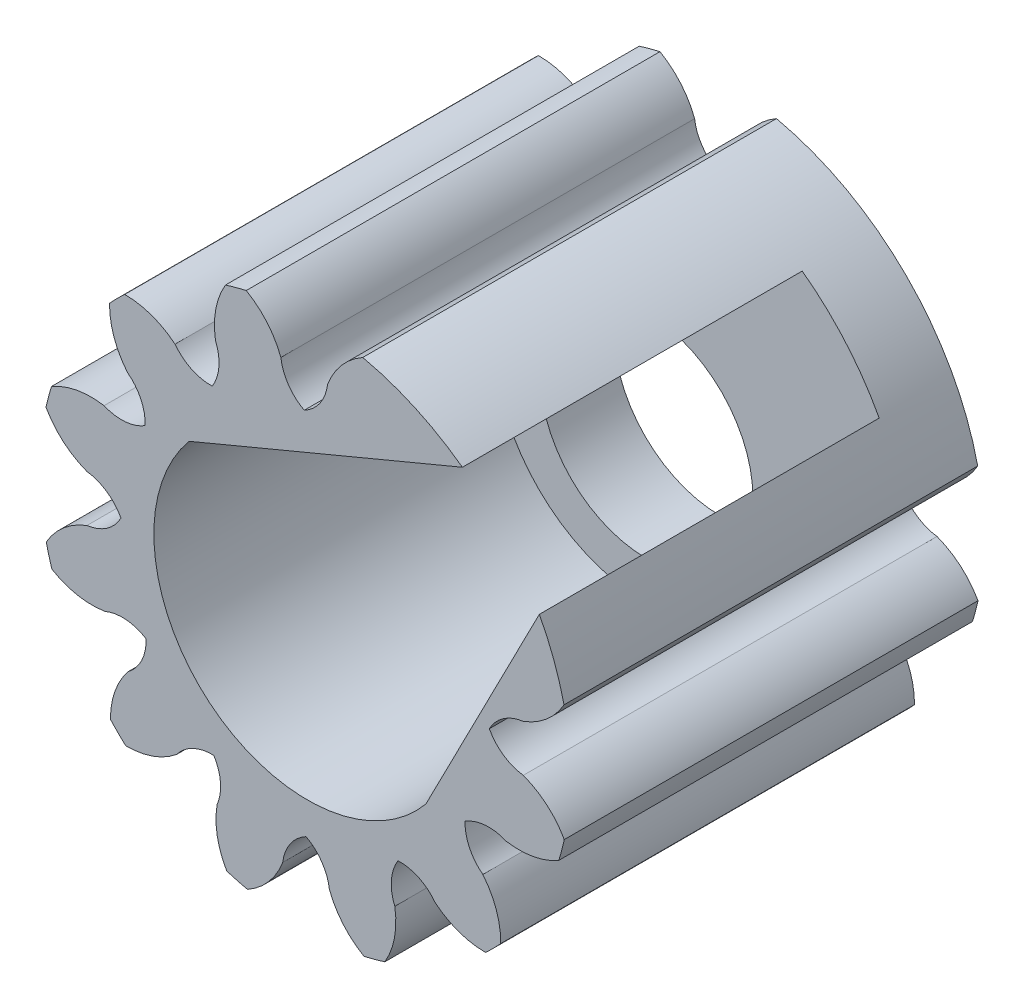
SolidWorks part; units mm, degrees
ref_plane "Front Plane" through (0, 0, 0) normal (0, 0, 1) x (1, 0, 0)
ref_plane "Top Plane" through (0, 0, 0) normal (0, 1, 0) x (1, 0, 0)
ref_plane "Right Plane" through (0, 0, 0) normal (1, 0, 0) x (0, 0, -1)
sketch "Sketch1" plane through (0, 0, 0) normal (0, 0, 1) x (1, 0, 0)
  circle A3 centre (0, 0) radius 8.9834
extrude "Boss-Extrude2" add sketch "Sketch1" against normal blind 14
sketch "Sketch2" plane through (0, 0, 0) normal (0, 0, 1) x (1, 0, 0)
  line L4 (-3.9288, 3.3744) -> (5.3214, 7.2377)
  line L6 (4.0872, -3.2476) -> (7.9252, 4.2299)
  arc A2 (-3.9288, 3.3744) -> (4.0872, -3.2476) centre (0.0792, 0.0634) ccw
  circle A3 centre (0, 0) radius 8.9834 construction
  arc A4 (5.3214, 7.2377) -> (7.9252, 4.2299) centre (0, 0) cw
  point P0 (5.3214, 7.2377)
extrude "Cut-Extrude1" cut sketch "Sketch2" against normal blind 11.5
sketch "Sketch9" plane through (0, 0, 0) normal (0, 0, 1) x (1, 0, 0)
  circle A0 centre (0.051, -0.2202) radius 3.6
  dimension "D1" = 7.2
extrude "Cut-Extrude4" cut sketch "Sketch9" against normal blind 14
sketch "Sketch10" plane through (0, 0, 0) normal (0, 0, 1) x (1, 0, 0)
  line L0 (-0.0306, -5.0091) -> (-0.0306, 10.9587) construction
  arc A0 (-0.0306, 6.2325) -> (0.7594, 7.3825) centre (-0.7394, 7.5658) ccw
  arc A1 (0.7594, 7.3825) -> (2.0694, 8.8325) centre (3.2502, 6.449) cw
  arc A2 (-0.0306, 6.2325) -> (-0.8206, 7.3825) centre (0.6782, 7.5658) cw
  arc A3 (-0.8206, 7.3825) -> (-2.1306, 8.8325) centre (-3.3114, 6.449) ccw
  arc A4 (-2.1306, 8.8325) -> (2.0694, 8.8325) centre (-0.0306, -5.0091) cw
  dimension "D1" = 2.66
  dimension "D2" = 1.51
  dimension "D3" = 1.45
  dimension "D4" = 1.31
  dimension "D5" = 1.15
  dimension "D6" = 0.79
extrude "Cut-Extrude5" cut sketch "Sketch10" against normal blind 14
pattern_circular "CirPattern2" count 10 every 30 about axis through (0, 0, 0) along (0, 0, 1) of "Cut-Extrude5"
